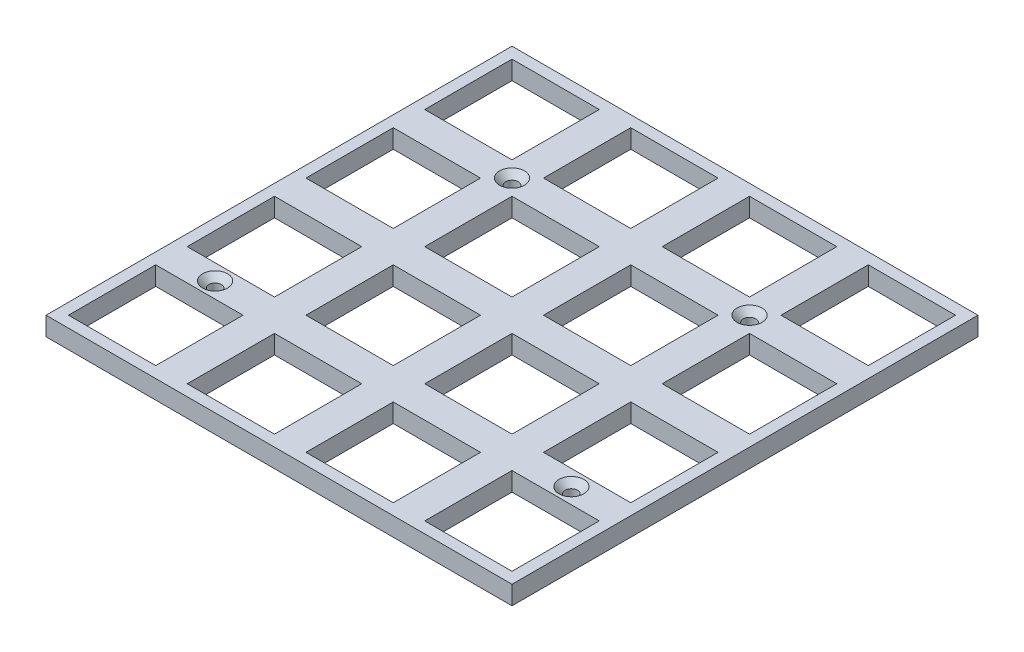
SolidWorks part; units mm, degrees
ref_plane "Front Plane" through (0, 0, 0) normal (0, 0, 1) x (1, 0, 0)
ref_plane "Top Plane" through (0, 0, 0) normal (0, 1, 0) x (1, 0, 0)
ref_plane "Right Plane" through (0, 0, 0) normal (1, 0, 0) x (0, 0, -1)
sketch "Sketch5" plane through (0, 0, 0) normal (1, 0, 0) x (0, 0, -1)
  line L0 (0, 0) -> (0, 13.4604) construction
sketch "Sketch1" plane through (0, 0, 0) normal (0, 1, 0) x (1, 0, 0)
  line L5 (-16.525, 21.575) -> (-16.525, 35.575)
  line L6 (-37.575, -37.575) -> (37.575, -37.575)
  line L11 (-37.575, -37.575) -> (-37.575, 37.575)
  line L12 (-37.575, 37.575) -> (37.575, 37.575)
  line L72 (37.575, -37.575) -> (37.575, 37.575)
  line L88 (-37.575, -37.575) -> (37.575, 37.575) construction
  line L89 (-37.575, 37.575) -> (37.575, -37.575) construction
  line L90 (-35.575, 21.575) -> (-21.575, 21.575)
  line L91 (-35.575, 21.575) -> (-35.575, 35.575)
  line L92 (-35.575, 35.575) -> (-21.575, 35.575)
  line L93 (-21.575, 21.575) -> (-21.575, 35.575)
  line L94 (-35.575, 21.575) -> (-21.575, 35.575) construction
  line L95 (-35.575, 35.575) -> (-21.575, 21.575) construction
  line L96 (-16.525, 21.575) -> (-2.525, 21.575)
  line L97 (-2.525, 21.575) -> (-2.525, 35.575)
  line L98 (-16.525, 35.575) -> (-2.525, 35.575)
  line L99 (2.525, 21.575) -> (2.525, 35.575)
  line L100 (2.525, 21.575) -> (16.525, 21.575)
  line L101 (16.525, 21.575) -> (16.525, 35.575)
  line L102 (2.525, 35.575) -> (16.525, 35.575)
  line L103 (21.575, 21.575) -> (21.575, 35.575)
  line L104 (21.575, 21.575) -> (35.575, 21.575)
  line L105 (35.575, 21.575) -> (35.575, 35.575)
  line L106 (21.575, 35.575) -> (35.575, 35.575)
  line L107 (-16.525, 2.525) -> (-16.525, 16.525)
  line L108 (-16.525, 2.525) -> (-2.525, 2.525)
  line L109 (-2.525, 2.525) -> (-2.525, 16.525)
  line L110 (-16.525, 16.525) -> (-2.525, 16.525)
  line L111 (2.525, 2.525) -> (2.525, 16.525)
  line L112 (2.525, 2.525) -> (16.525, 2.525)
  line L113 (16.525, 2.525) -> (16.525, 16.525)
  line L114 (2.525, 16.525) -> (16.525, 16.525)
  line L115 (21.575, 2.525) -> (21.575, 16.525)
  line L116 (21.575, 2.525) -> (35.575, 2.525)
  line L117 (35.575, 2.525) -> (35.575, 16.525)
  line L118 (21.575, 16.525) -> (35.575, 16.525)
  line L119 (-16.525, -16.525) -> (-16.525, -2.525)
  line L120 (-16.525, -16.525) -> (-2.525, -16.525)
  line L121 (-2.525, -16.525) -> (-2.525, -2.525)
  line L122 (-16.525, -2.525) -> (-2.525, -2.525)
  line L123 (2.525, -16.525) -> (2.525, -2.525)
  line L124 (2.525, -16.525) -> (16.525, -16.525)
  line L125 (16.525, -16.525) -> (16.525, -2.525)
  line L126 (2.525, -2.525) -> (16.525, -2.525)
  line L127 (21.575, -16.525) -> (21.575, -2.525)
  line L128 (21.575, -16.525) -> (35.575, -16.525)
  line L129 (35.575, -16.525) -> (35.575, -2.525)
  line L130 (21.575, -2.525) -> (35.575, -2.525)
  line L131 (-16.525, -35.575) -> (-16.525, -21.575)
  line L132 (-16.525, -35.575) -> (-2.525, -35.575)
  line L133 (-2.525, -35.575) -> (-2.525, -21.575)
  line L134 (-16.525, -21.575) -> (-2.525, -21.575)
  line L135 (2.525, -35.575) -> (2.525, -21.575)
  line L136 (2.525, -35.575) -> (16.525, -35.575)
  line L137 (16.525, -35.575) -> (16.525, -21.575)
  line L138 (2.525, -21.575) -> (16.525, -21.575)
  line L139 (21.575, -35.575) -> (21.575, -21.575)
  line L140 (21.575, -35.575) -> (35.575, -35.575)
  line L141 (35.575, -35.575) -> (35.575, -21.575)
  line L142 (21.575, -21.575) -> (35.575, -21.575)
  line L143 (-35.575, 2.525) -> (-35.575, 16.525)
  line L144 (-35.575, 2.525) -> (-21.575, 2.525)
  line L145 (-21.575, 2.525) -> (-21.575, 16.525)
  line L146 (-35.575, 16.525) -> (-21.575, 16.525)
  line L147 (-35.575, -16.525) -> (-35.575, -2.525)
  line L148 (-35.575, -16.525) -> (-21.575, -16.525)
  line L149 (-21.575, -16.525) -> (-21.575, -2.525)
  line L150 (-35.575, -2.525) -> (-21.575, -2.525)
  line L151 (-35.575, -35.575) -> (-35.575, -21.575)
  line L152 (-35.575, -35.575) -> (-21.575, -35.575)
  line L153 (-21.575, -35.575) -> (-21.575, -21.575)
  line L154 (-35.575, -21.575) -> (-21.575, -21.575)
  line L155 (-35.575, 21.575) -> (-16.525, 21.575) construction
  line L156 (-35.575, 21.575) -> (-35.575, 2.525) construction
  point P0 (0, 0)
  point P6 (-28.575, 28.575)
  dimension "D1" = 2
  dimension "D2" = 14
  dimension "D5" = 90
  dimension "D6" = 19.05
  dimension "D7" = 19.05
  dimension "D3" = 4
  dimension "D8" = 75.15
  dimension "D9" = 5.05
  dimension "D4" = 4
extrude "Boss-Extrude1" add sketch "Sketch1" along normal blind 3
sketch "Sketch2" plane through (0, 3, 0) normal (0, 1, 0) x (1, 0, 0)
  line L0 (-28.575, -16.525) -> (-28.575, -21.575) construction
  line L5 (-35.575, -16.525) -> (-21.575, -16.525) construction
  line L7 (-21.575, -21.575) -> (-35.575, -21.575) construction
  line L8 (-28.575, -19.05) -> (0, -19.05) construction
  line L9 (-21.575, 16.525) -> (-16.525, 16.525) construction
  line L10 (-21.575, 16.525) -> (-21.575, 21.575) construction
  line L11 (-21.575, 21.575) -> (-16.525, 21.575) construction
  line L12 (-16.525, 16.525) -> (-16.525, 21.575) construction
  line L15 (-21.575, 16.525) -> (-16.525, 21.575) construction
  line L20 (-21.575, 21.575) -> (-16.525, 16.525) construction
  line L22 (-19.05, 19.05) -> (0, 19.05) construction
  circle A0 centre (-19.05, 19.05) radius 1
  circle A1 centre (-28.575, -19.05) radius 1
  point P8 (-19.05, 19.05)
  point P17 (-28.575, -19.05)
  dimension "D1" = 2
  dimension "D2" = 2
  dimension "D3" = 19.05
  dimension "D4" = 28.575
extrude "Cut-Extrude1" cut sketch "Sketch2" against normal up to surface (3 mm away) up to face at (0, 0, 0)
sketch "Sketch3" plane through (0, 3, 0) normal (0, 1, 0) x (1, 0, 0)
  circle A2 centre (-19.05, 19.05) radius 2
  circle A3 centre (-19.05, 19.05) radius 2
  circle A4 centre (-28.575, -19.05) radius 2
  circle A5 centre (-28.575, -19.05) radius 2
  dimension "D1" = 1
  dimension "D2" = 1
extrude "Cut-Extrude2" [suppressed] cut sketch "Sketch3" against normal blind 1
chamfer "Chamfer1" distance 1 angle 45 2 edges at (-19.05, 3, -18.05) (-28.575, 3, 20.05)
mirror "Mirror1" about plane through (0, 0, 0) normal (1, 0, 0) of "Chamfer1", "Cut-Extrude1"
other "Move Face1" face at (37.575, 1.5, 0) face at (0, 1.5, -37.575) face at (0, 1.5, 37.575) face at (-37.575, 1.5, 0) parameters "D1"=0.2
equation "\"screwhole\"=2"
equation "\"D2@Sketch2\"=\"screwhole\""
equation "\"D1@Sketch2\"=\"screwhole\""
